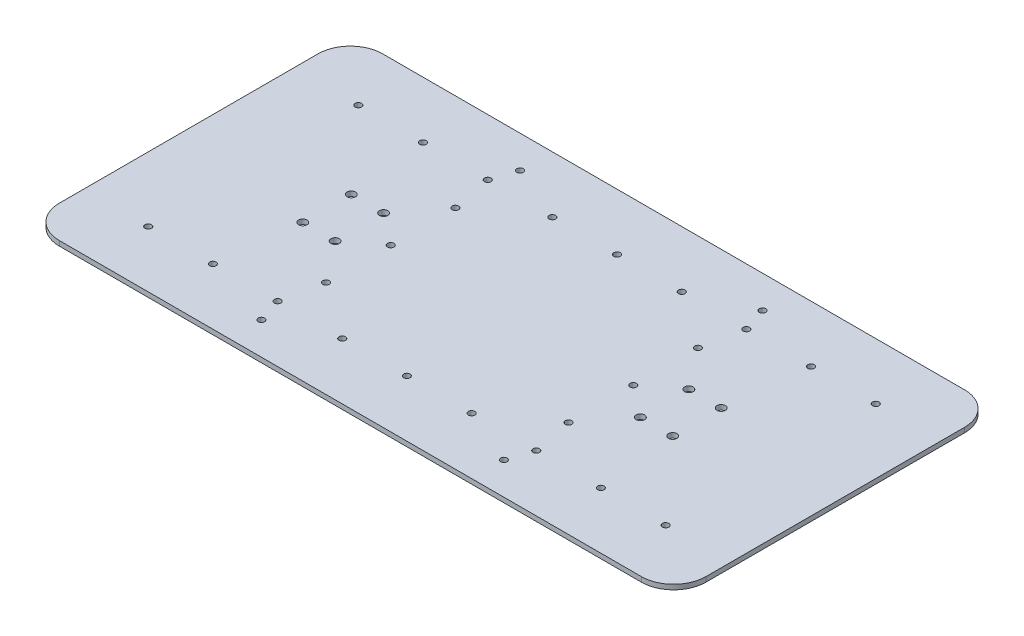
SolidWorks part; units mm, degrees
ref_plane "前视基准面" through (0, 0, 0) normal (0, 0, 1) x (1, 0, 0)
ref_plane "上视基准面" through (0, 0, 0) normal (0, 1, 0) x (1, 0, 0)
ref_plane "右视基准面" through (0, 0, 0) normal (1, 0, 0) x (0, 0, -1)
sketch "草图1" plane through (0, 0, 0) normal (0, 1, 0) x (1, 0, 0)
  line L1 (180, -100) -> (-180, -100)
  line L2 (200, -80) -> (200, 80)
  line L3 (180, 100) -> (-180, 100)
  line L4 (-200, -80) -> (-200, 80)
  line L5 (200, -100) -> (-200, 100) construction
  line L6 (200, 100) -> (-200, -100) construction
  arc A0 (-180, 100) -> (-200, 80) centre (-180, 80) ccw
  arc A1 (-200, -80) -> (-180, -100) centre (-180, -80) ccw
  arc A2 (200, 80) -> (180, 100) centre (180, 80) ccw
  arc A3 (200, -80) -> (180, -100) centre (180, -80) cw
  point P0 (0, 0)
  dimension "D1" = 20
extrude "凸台-拉伸2" add sketch "草图1" along normal blind 3
sketch "草图2" plane through (0, 0, 0) normal (0, 1, 0) x (1, 0, 0)
  circle A0 centre (-114.4, 15) radius 2.6
extrude "切除-拉伸3" cut sketch "草图2" against normal through all and the other way blind 10
sketch "草图3" plane through (0, 3, 0) normal (0, 1, 0) x (1, 0, 0)
  circle A0 centre (-114.4, -15) radius 2.6
  circle A1 centre (-94.4, 15) radius 2.6
  circle A3 centre (-114.4, 15) radius 2.6 construction
  circle A4 centre (-94.4, -15) radius 2.6
  circle A6 centre (114.4, 15) radius 2.6
  circle A8 centre (94.4, 15) radius 2.6
  circle A9 centre (94.4, -15) radius 2.6
  circle A10 centre (114.4, -15) radius 2.6
  dimension "D1" = 20
  dimension "D2" = 30
extrude "切除-拉伸4" cut sketch "草图3" against normal blind 3
sketch "草图4" plane through (0, 0, 0) normal (0, 1, 0) x (1, 0, 0)
  circle A1 centre (-160, 65) radius 2
  circle A6 centre (-40, 65) radius 2
  circle A8 centre (0, 65) radius 2
  circle A10 centre (40, 65) radius 2
  circle A13 centre (80, 65) radius 2
  circle A15 centre (120, 65) radius 2
  circle A17 centre (160, 65) radius 2
  circle A19 centre (-160, -65) radius 2
  circle A22 centre (-120, 65) radius 2
  circle A23 centre (-80, 65) radius 2
  circle A24 centre (-120, -65) radius 2
  circle A25 centre (-80, -65) radius 2
  circle A26 centre (-40, -65) radius 2
  circle A27 centre (0, -65) radius 2
  circle A28 centre (40, -65) radius 2
  circle A29 centre (80, -65) radius 2
  circle A30 centre (120, -65) radius 2
  circle A31 centre (160, -65) radius 2
  point P8 (0, 0)
  dimension "D1" = 9
extrude "切除-拉伸29" cut sketch "草图4" against normal blind 3 and the other way blind 10 contours A17
sketch "草图5" plane through (0, 3, 0) normal (0, 1, 0) x (1, 0, 0)
  circle A0 centre (-160, -65) radius 2
  circle A1 centre (-120, -65) radius 2
  circle A2 centre (-80, -65) radius 2
  circle A3 centre (-40, -65) radius 2
  circle A4 centre (0, -65) radius 2
  circle A5 centre (40, -65) radius 2
  circle A6 centre (80, -65) radius 2
  circle A7 centre (120, -65) radius 2
  circle A8 centre (160, -65) radius 2
extrude "切除-拉伸30" cut sketch "草图5" against normal blind 3
sketch "草图6" plane through (0, 3, 0) normal (0, 1, 0) x (1, 0, 0)
  circle A0 centre (-160, 65) radius 2
  circle A1 centre (-120, 65) radius 2
  circle A2 centre (-80, 65) radius 2
  circle A3 centre (-40, 65) radius 2
  circle A4 centre (0, 65) radius 2
  circle A5 centre (40, 65) radius 2
  circle A6 centre (80, 65) radius 2
  circle A7 centre (120, 65) radius 2
extrude "切除-拉伸31" cut sketch "草图6" against normal blind 3
sketch "草图7" plane through (0, 3, 0) normal (0, 1, 0) x (1, 0, 0)
  circle A0 centre (-75, -80) radius 2
  point P2 (0, 0)
extrude "切除-拉伸32" cut sketch "草图7" against normal blind 3
sketch "草图8" plane through (0, 3, 0) normal (0, 1, 0) x (1, 0, 0)
  circle A0 centre (-75, 80) radius 2
  circle A1 centre (-75, 40) radius 2
  circle A2 centre (-75, 0) radius 2
  circle A3 centre (-75, -40) radius 2
  point P8 (0, 0)
extrude "切除-拉伸33" cut sketch "草图8" against normal blind 3
sketch "草图9" plane through (0, 3, 0) normal (0, 1, 0) x (1, 0, 0)
  circle A0 centre (75, 80) radius 2
  circle A2 centre (75, 40) radius 2
  circle A3 centre (75, 0) radius 2
  circle A4 centre (75, -40) radius 2
  circle A5 centre (75, -80) radius 2
extrude "切除-拉伸34" cut sketch "草图9" against normal blind 3
